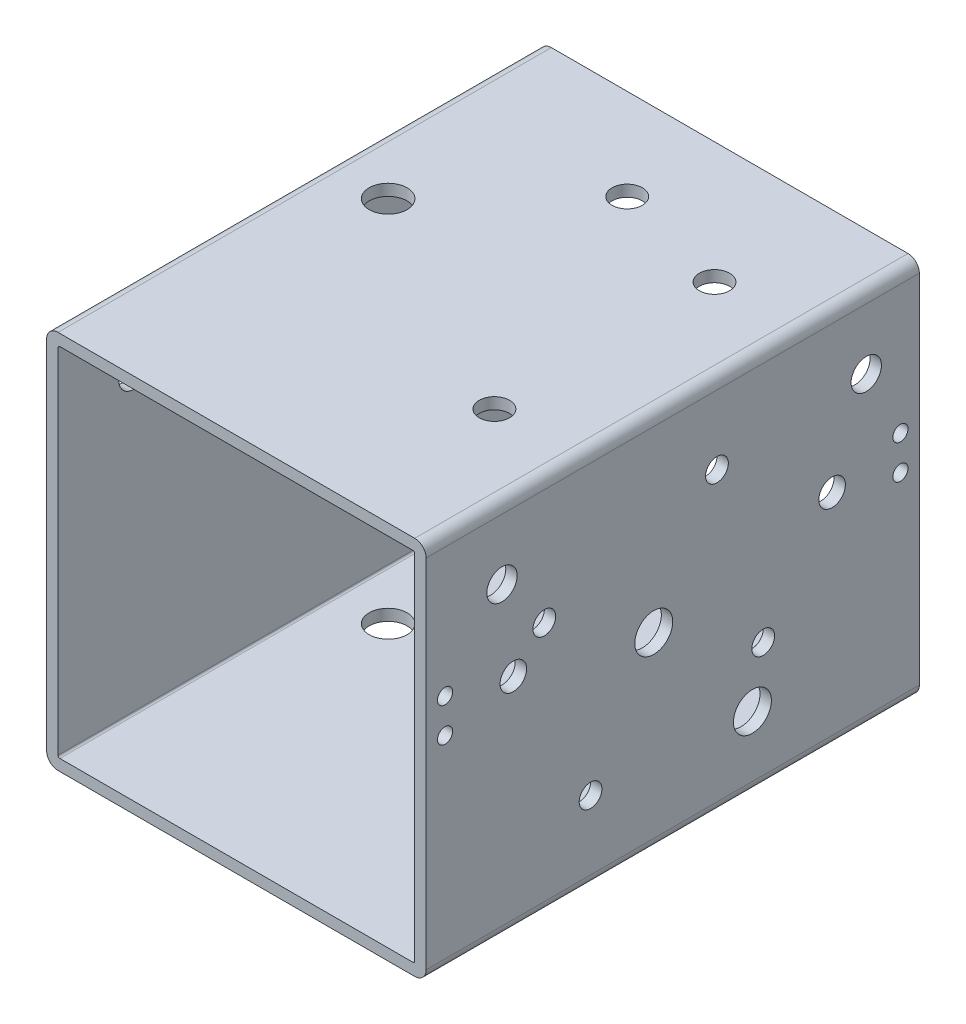
SolidWorks part; units mm, degrees
ref_plane "Front Plane" through (0, 0, 0) normal (0, 0, 1) x (1, 0, 0)
ref_plane "Top Plane" through (0, 0, 0) normal (0, 1, 0) x (1, 0, 0)
ref_plane "Right Plane" through (0, 0, 0) normal (1, 0, 0) x (0, 0, -1)
sketch "Sketch1" plane through (0, 0, 0) normal (0, 0, 1) x (1, 0, 0)
  line L1 (-50, 50) -> (50, 50)
  line L2 (-50, 50) -> (-50, -50)
  line L3 (-50, -50) -> (50, -50)
  line L4 (50, 50) -> (50, -50)
  line L5 (-50, 50) -> (50, -50) construction
  line L6 (-50, -50) -> (50, 50) construction
  point P0 (0, 0)
  dimension "D1" = 100
  dimension "D2" = 100
extrude "Extrude-Thin1" add sketch "Sketch1" along normal blind 130 thin
fillet "Fillet1" radius 0.5 4 edges at (-47, -47, 65) (-47, 47, 65) (47, 47, 65) (47, -47, 65)
fillet "Fillet2" radius 3 4 edges at (50, -50, 65) (-50, -50, 65) (50, 50, 65) (-50, 50, 65)
sketch "Holes - top" plane through (0, 0, 0) normal (0, 1, 0) x (1, 0, 0)
  line L0 (-3, 0) -> (-3, -130) construction
  line L1 (47, -130) -> (-47, -130) construction
  line L2 (-23, 0) -> (-23, -130) construction
  line L3 (47, 0) -> (-47, 0) construction
  line L4 (17, 0) -> (17, -130) construction
  circle A0 centre (-34, -56) radius 11 construction
  circle A1 centre (28, -90) radius 11 construction
  circle A2 centre (28, -32) radius 11 construction
  dimension "D4" = 22
  dimension "D1" = 40
  dimension "D2" = 40
  dimension "D3" = 32
  dimension "D5" = 56
  dimension "D6" = 3
hole_wizard "Ø8.0 (8) Diameter Hole2" positions "Sketch6" profile "Sketch5" hole size "Ø8.0" standard "ANSI Metric" end condition through all
sketch "Sketch6" plane through (0, 50, 0) normal (0, 1, 0) x (1, 0, 0)
  point P0 (28, -32)
  point P6 (28, -90)
sketch "Sketch5" plane through (28, 50, 32) normal (1, 0, 0) x (0, 0, 1)
  line L0 (0, 0) -> (0, 100)
  line L1 (0, 100) -> (4, 100)
  line L2 (4, 100) -> (4, 0)
  line L5 (4, 0) -> (0, 0)
  line L11 (0, -6.35) -> (0, 107.95) construction
  dimension "Thru Hole Dia." = 8
  dimension "Thru Hole Depth" = 100
sketch "Holes - side" plane through (0, 0, 0) normal (1, 0, 0) x (0, 0, -1)
  line L0 (0, 0) -> (-130, 0) construction
  line L1 (-130, -47) -> (-130, 47) construction
  line L2 (-130, 20) -> (0, 20) construction
  line L3 (0, -47) -> (0, 47) construction
  line L4 (-130, -20) -> (0, -20) construction
  circle A0 centre (-110, 31) radius 11 construction
  circle A1 centre (-14, 31) radius 11 construction
  circle A2 centre (-44, -31) radius 11 construction
  dimension "D1" = 40
  dimension "D2" = 22
  dimension "D3" = 20
  dimension "D4" = 14
  dimension "D5" = 44
hole_wizard "Ø8.0 (8) Diameter Hole3" positions "Sketch9" profile "Sketch8" hole size "Ø8.0" standard "ANSI Metric" end condition through all
sketch "Sketch9" plane through (50, 0, 0) normal (1, 0, 0) x (0, 0, -1)
  point P0 (-14, 31)
  point P3 (-110, 31)
sketch "Sketch8" plane through (50, 31, 14) normal (0, 1, 0) x (0, 0, -1)
  line L0 (0, 0) -> (0, 100)
  line L1 (0, 100) -> (4, 100)
  line L2 (4, 100) -> (4, 0)
  line L5 (4, 0) -> (0, 0)
  line L11 (0, -6.35) -> (0, 107.95) construction
  dimension "Thru Hole Dia." = 8
  dimension "Thru Hole Depth" = 100
hole_wizard "Ø10.0 (10) Diameter Hole1" positions "Sketch12" profile "Sketch11" hole size "Ø10.0" standard "ANSI Metric" end condition through all
sketch "Sketch12" plane through (0, 50, 0) normal (0, 1, 0) x (1, 0, 0)
  point P0 (-34, -56)
sketch "Sketch11" plane through (-34, 50, 56) normal (1, 0, 0) x (0, 0, 1)
  line L0 (0, 0) -> (0, 100)
  line L1 (0, 100) -> (5, 100)
  line L2 (5, 100) -> (5, 0)
  line L5 (5, 0) -> (0, 0)
  line L11 (0, -6.35) -> (0, 107.95) construction
  dimension "Thru Hole Dia." = 10
  dimension "Thru Hole Depth" = 100
hole_wizard "Ø10.0 (10) Diameter Hole2" positions "Sketch14" profile "Sketch13" hole size "Ø10.0" standard "ANSI Metric" end condition through all
sketch "Sketch14" plane through (50, 0, 0) normal (1, 0, 0) x (0, 0, -1)
  point P0 (-44, -31)
sketch "Sketch13" plane through (50, -31, 44) normal (0, 1, 0) x (0, 0, -1)
  line L0 (0, 0) -> (0, 100)
  line L1 (0, 100) -> (5, 100)
  line L2 (5, 100) -> (5, 0)
  line L5 (5, 0) -> (0, 0)
  line L11 (0, -6.35) -> (0, 107.95) construction
  dimension "Thru Hole Dia." = 10
  dimension "Thru Hole Depth" = 100
hole_wizard "M8x1.25 Tapped Hole1" positions "Sketch18" profile "Sketch17" tap size "M8x1.25" standard "ANSI Metric"
sketch "Sketch18" plane through (-50, 0, 0) normal (-1, 0, 0) x (0, 0, 1)
  line L0 (56, 35) -> (56, -15) construction
  point P0 (56, -15)
  point P2 (56, 35)
  dimension "D1" = 56
  dimension "D2" = 35
  dimension "D3" = 15
sketch "Sketch17" plane through (-50, -15, 56) normal (0, 1, 0) x (0, 0, 1)
  line L0 (0, 0) -> (0, 3)
  line L1 (0, 3) -> (3.4, 3)
  line L2 (3.4, 3) -> (3.4, 0)
  line L5 (3.4, 0) -> (0, 0)
  line L11 (0, -6.35) -> (0, 107.95) construction
  dimension "Thru Tap Drill Dia." = 6.8
  dimension "Thru Tap Drill Depth" = 3
cosmetic thread "Hole Thread1" parameters "D2"=8
cosmetic thread "Hole Thread2" parameters "D2"=8
hole_wizard "M8x1.25 Tapped Hole2" positions "Sketch21" profile "Sketch20" tap size "M8x1.25" standard "ANSI Metric"
sketch "Sketch21" plane through (0, -50, 0) normal (0, -1, 0) x (-1, 0, 0)
  line L0 (20, -44) -> (-35, -44) construction
  point P0 (20, -44)
  point P2 (-35, -44)
  dimension "D1" = 44
  dimension "D2" = 35
  dimension "D3" = 20
sketch "Sketch20" plane through (-20, -50, 44) normal (1, 0, 0) x (0, 0, -1)
  line L0 (0, 0) -> (0, 3)
  line L1 (0, 3) -> (3.4, 3)
  line L2 (3.4, 3) -> (3.4, 0)
  line L5 (3.4, 0) -> (0, 0)
  line L11 (0, -6.35) -> (0, 107.95) construction
  dimension "Thru Tap Drill Dia." = 6.8
  dimension "Thru Tap Drill Depth" = 3
cosmetic thread "Hole Thread3" parameters "D2"=8
cosmetic thread "Hole Thread4" parameters "D2"=8
sketch "Holes - Nema 23 motor" plane through (0, 0, 0) normal (1, 0, 0) x (0, 0, -1)
  line L0 (-98.8427, 16.6524) -> (-53.3476, 28.8427) construction
  line L1 (-98.8427, 16.6524) -> (-86.6524, -28.8427) construction
  line L2 (-53.3476, 28.8427) -> (-41.1573, -16.6524) construction
  line L3 (-86.6524, -28.8427) -> (-41.1573, -16.6524) construction
  line L4 (-98.8427, 16.6524) -> (-41.1573, -16.6524) construction
  line L5 (-53.3476, 28.8427) -> (-86.6524, -28.8427) construction
  line L6 (0, 0) -> (-130, 0) construction
  point P1 (-70, 0)
  dimension "D1" = 70
  dimension "D2" = 47.1
  dimension "D3" = 47.1
  dimension "D4" = 15
hole_wizard "Ø10.0 (10) Diameter Hole3" positions "Sketch24" profile "Sketch23" hole size "Ø10.0" standard "ANSI Metric"
sketch "Sketch24" plane through (50, 0, 0) normal (1, 0, 0) x (0, 0, -1)
  point P0 (-70, 0)
sketch "Sketch23" plane through (50, 0, 70) normal (0, 1, 0) x (0, 0, -1)
  line L0 (0, 0) -> (0, 3)
  line L1 (0, 3) -> (5, 3)
  line L2 (5, 3) -> (5, 0)
  line L5 (5, 0) -> (0, 0)
  line L11 (0, -6.35) -> (0, 107.95) construction
  dimension "Thru Hole Dia." = 10
  dimension "Thru Hole Depth" = 3
hole_wizard "Ø6.0 (6) Diameter Hole1" positions "Sketch26" profile "Sketch25" hole size "Ø6.0" standard "ANSI Metric"
sketch "Sketch26" plane through (50, 0, 0) normal (1, 0, 0) x (0, 0, -1)
  point P0 (-41.1573, -16.6524)
  point P3 (-53.3476, 28.8427)
  point P6 (-98.8427, 16.6524)
  point P9 (-86.6524, -28.8427)
sketch "Sketch25" plane through (50, -16.6524, 41.1573) normal (0, 1, 0) x (0, 0, -1)
  line L0 (0, 0) -> (0, 3)
  line L1 (0, 3) -> (3, 3)
  line L2 (3, 3) -> (3, 0)
  line L5 (3, 0) -> (0, 0)
  line L11 (0, -6.35) -> (0, 107.95) construction
  dimension "Thru Hole Dia." = 6
  dimension "Thru Hole Depth" = 3
hole_wizard "Ø8.0 (8) Diameter Hole4" positions "Sketch29" profile "Sketch28" hole size "Ø8.0" standard "ANSI Metric"
sketch "Sketch29" plane through (0, 50, 0) normal (0, 1, 0) x (1, 0, 0)
  line L0 (-3, 0) -> (-3, -130) construction
  point P0 (-3, -24)
  dimension "D2" = 8
sketch "Sketch28" plane through (-3, 50, 24) normal (1, 0, 0) x (0, 0, 1)
  line L0 (0, 0) -> (0, 3)
  line L1 (0, 3) -> (4, 3)
  line L2 (4, 3) -> (4, 0)
  line L5 (4, 0) -> (0, 0)
  line L11 (0, -6.35) -> (0, 107.95) construction
  dimension "Thru Hole Dia." = 8
  dimension "Thru Hole Depth" = 3
sketch "Sketch31" plane through (50, 0, 0) normal (1, 0, 0) x (0, 0, -1)
  line L0 (0, -47) -> (0, 47) construction
  line L1 (-130, 50) -> (0, 50) construction
  line L2 (-65, 117.0212) -> (-65, -118.5233) construction
  line L3 (-130, -47) -> (-130, 47) construction
  circle A0 centre (-5, 4) radius 2
  circle A1 centre (-5, 13) radius 2
  circle A2 centre (-125, 13) radius 2
  circle A3 centre (-125, 4) radius 2
  circle A4 centre (-23, 8.5) radius 3.5
  circle A5 centre (-107, 8.5) radius 3.5
  dimension "D1" = 4
  dimension "D2" = 4
  dimension "D3" = 9
  dimension "D4" = 5
  dimension "D5" = 46
  dimension "D6" = 5
  dimension "D8" = 7
  dimension "D9" = 18
  dimension "D7" = 65
  dimension "D10" = 4.5
extrude "Cut-Extrude1" cut sketch "Sketch31" against normal up to next
equation "\"a\"= \"Trolley Profile@Plasma Beta.Assembly\""
equation "\"b\"= \"Trolley Profile Thickness@Plasma Beta.Assembly\""
equation "\"L\"= 130"
equation "\"D2@Sketch1\"=\"a\""
equation "\"D1@Sketch1\"=\"a\""
equation "\"D1@Extrude-Thin1\"=\"L\""
equation "\"D5@Extrude-Thin1\"=\"b\""
equation "\"D1@Fillet2\"=\"b\""
equation "\"d-bearing\"= 22'diameter of bearing"
equation "\"a-small\"= \"Beam Profile@Plasma Beta.Assembly\"'profile of smaller beam"
equation "\"D4@Holes - top\"=\"d-bearing\""
equation "\"D2@Holes - side\"=\"d-bearing\""
equation "\"D1@Holes - top\"=\"a-small\""
equation "\"D1@Holes - side\"=\"a-small\""
